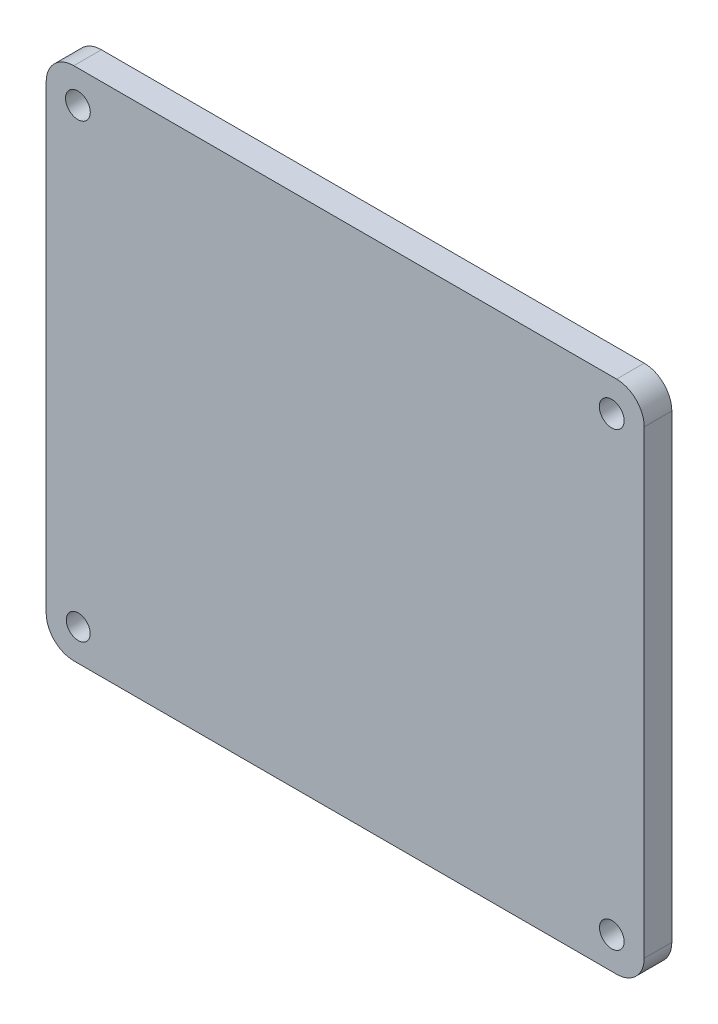
SolidWorks part; units mm, degrees
material "Plastique personnalisé"
ref_plane "Plan de face" through (0, 0, 0) normal (0, 0, 1) x (1, 0, 0)
ref_plane "Plan de dessus" through (0, 0, 0) normal (0, 1, 0) x (1, 0, 0)
ref_plane "Plan de droite" through (0, 0, 0) normal (1, 0, 0) x (0, 0, -1)
sketch "Esquisse1" plane through (0, 0, 0) normal (0, 0, 1) x (1, 0, 0)
  line L0 (139.887, 293.2101) -> (204.887, 293.2101) construction
  line L1 (142.9143, 306.3335) -> (201.8719, 306.3335)
  line L2 (204.8719, 303.3335) -> (204.8719, 253.3481)
  line L3 (201.8719, 250.3481) -> (142.9143, 250.3481)
  line L4 (139.9143, 253.3481) -> (139.9143, 303.3335)
  arc A0 (204.8719, 253.3481) -> (201.8719, 250.3481) centre (201.8719, 253.3481) cw
  arc A1 (201.8719, 306.3335) -> (204.8719, 303.3335) centre (201.8719, 303.3335) cw
  arc A2 (142.9143, 250.3481) -> (139.9143, 253.3481) centre (142.9143, 253.3481) cw
  arc A3 (142.9143, 306.3335) -> (139.9143, 303.3335) centre (142.9143, 303.3335) ccw
  circle A4 centre (143.3605, 302.8316) radius 1.3453
  circle A5 centre (201.3447, 302.8186) radius 1.3469
  circle A6 centre (143.3955, 253.802) radius 1.2986
  circle A7 centre (201.3549, 253.8151) radius 1.3357
  dimension "D2" = 3
  dimension "D1" = 65
extrude "Boss.-Extru.1" add sketch "Esquisse1" along normal blind 3
